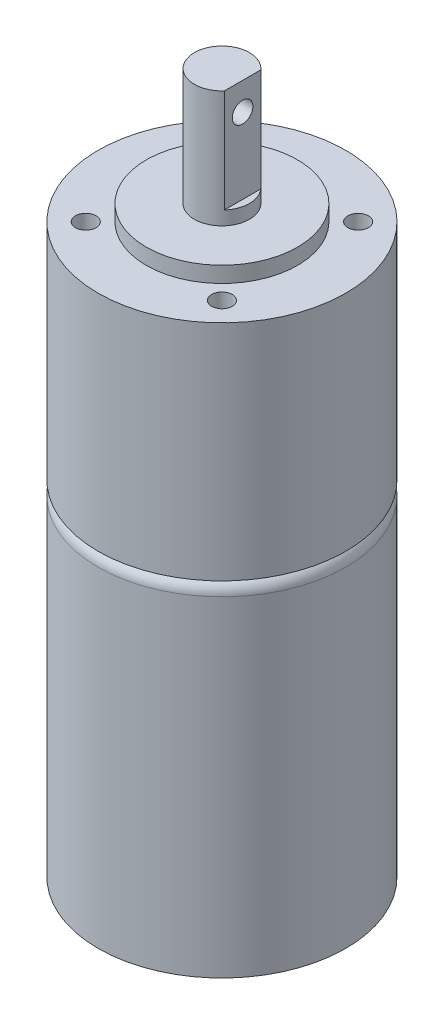
SolidWorks part; units mm, degrees
other "标注2"
sketch "草图13" plane through (18, 101.8, -18) normal (0.999, 0.0296, -0.0329) x (-0.0373, 0.1633, -0.9859)
ref_plane "前视基准面" through (0, 0, 0) normal (0, 0, 1) x (1, 0, 0)
ref_plane "上视基准面" through (0, 0, 0) normal (0, 1, 0) x (1, 0, 0)
ref_plane "右视基准面" through (0, 0, 0) normal (1, 0, 0) x (0, 0, -1)
other "Configuration Table"
sketch "草图3" plane through (0, 0, 0) normal (0, 1, 0) x (1, 0, 0)
  circle A0 centre (0, 0) radius 18
  dimension "D1" = 36
extrude "凸台-拉伸1" add sketch "草图3" along normal blind 50 contours A0
fillet "圆角2" radius 2 1 edges at (0, 50, 18)
sketch "草图4" plane through (0, 0, 0) normal (0, -1, 0) x (1, 0, 0)
  circle A0 centre (0, 0) radius 6.5
  dimension "D1" = 13
extrude "凸台-拉伸2" add sketch "草图4" along normal blind 3 contours A0
sketch "草图5" plane through (0, 50, 0) normal (0, 1, 0) x (1, 0, 0)
  circle A0 centre (0, 0) radius 18
extrude "凸台-拉伸3" add sketch "草图5" along normal blind 32.5 contours A0
sketch "草图6" plane through (0, 82.5, 0) normal (0, 1, 0) x (1, 0, 0)
  circle A0 centre (0, 0) radius 11
  dimension "D1" = 22
extrude "凸台-拉伸4" add sketch "草图6" along normal blind 2.3 contours A0
sketch "草图7" plane through (0, 84.8, 0) normal (0, 1, 0) x (1, 0, 0)
  circle A0 centre (0, 0) radius 4
  dimension "D1" = 8
extrude "凸台-拉伸5" add sketch "草图7" along normal blind 17 contours A0
sketch "草图8" plane through (0, 101.8, 0) normal (0, 1, 0) x (1, 0, 0)
  line L0 (-4, 0) -> (4, 0) construction
  line L1 (3, 2.6458) -> (3, -2.6458)
  circle A0 centre (0, 0) radius 4 construction
  arc A2 (3, 2.6458) -> (3, -2.6458) centre (0, 0) cw
  point P5 (3, 0)
  circle M3 centre (0, 0) radius 4
  dimension "D1" = 7
extrude "切除-拉伸1" cut sketch "草图8" against normal blind 15 contours L0 L1 M3 | L1 L0 A2
sketch "草图10" plane through (0, 82.5, 0) normal (0, 1, 0) x (1, 0, 0)
  line L0 (-18, 0) -> (18, 0) construction
  line L1 (0, 18) -> (0, -18) construction
  line L2 (0, 0) -> (12.7279, -12.7279) construction
  line L3 (0, 0) -> (-12.7279, 12.7279) construction
  line L4 (0, 0) -> (12.7279, 12.7279) construction
  line L5 (0, 0) -> (-12.7279, -12.7279) construction
  circle A0 centre (0, 0) radius 14
  circle A1 centre (0, 0) radius 18 construction
  circle A2 centre (-9.8995, 9.8995) radius 1.5
  circle A3 centre (9.8995, 9.8995) radius 1.5
  circle A4 centre (9.8995, -9.8995) radius 1.5
  circle A5 centre (-9.8995, -9.8995) radius 1.5
  dimension "D1" = 28
  dimension "D2" = 3
  dimension "D3" = 45
  dimension "D4" = 45
  dimension "D5" = 45
  dimension "D6" = 45
extrude "切除-拉伸2" cut sketch "草图10" against normal blind 8 contours A2 | A3 | A5 | A4
sketch "草图11" plane through (0, -3, 0) normal (0, -1, 0) x (1, 0, 0)
  circle A0 centre (0, 0) radius 1.585
  dimension "D1" = 3.17
extrude "凸台-拉伸6" add sketch "草图11" along normal blind 2
sketch "草图14" plane through (3, 0, 0) normal (1, 0, 0) x (0, 0, -1)
  line L0 (2.6458, 101.8) -> (-2.6458, 101.8) construction
  line L1 (0, 101.8) -> (0, 97.8) construction
  circle A0 centre (0, 97.8) radius 1.5
  dimension "D1" = 3
  dimension "D2" = 4
extrude "切除-拉伸3" cut sketch "草图14" against normal blind 7
